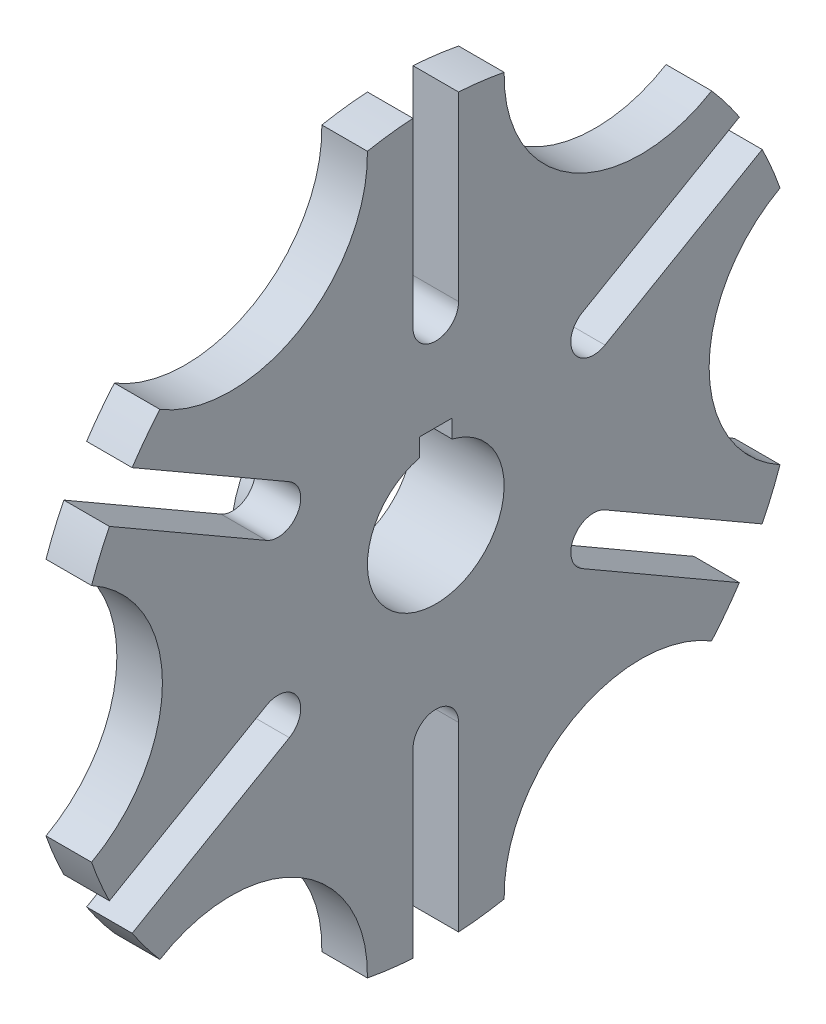
SolidWorks part; units mm, degrees
ref_plane "Front" through (0, 0, 0) normal (0, 0, 1) x (1, 0, 0)
ref_plane "Top" through (0, 0, 0) normal (0, 1, 0) x (1, 0, 0)
ref_plane "Right" through (0, 0, 0) normal (1, 0, 0) x (0, 0, -1)
sketch "Sketch1" plane through (0, 0, 0) normal (1, 0, 0) x (0, 0, -1)
  circle A0 centre (0, 0) radius 101.6
  dimension "D1" = 203.2
extrude "Boss-Extrude1" add sketch "Sketch1" along normal blind 12.7
sketch "Sketch2" plane through (12.7, 0, 0) normal (1, 0, 0) x (0, 0, -1)
  line L0 (0, 101.6) -> (0, 50.8) construction
  line L1 (6.35, 101.6) -> (6.35, 50.8)
  line L2 (-6.35, 101.6) -> (-6.35, 50.8)
  circle A0 centre (0, 0) radius 50.8 construction
  circle A1 centre (0, 0) radius 101.6 construction
  arc A3 (-6.35, 50.8) -> (6.35, 50.8) centre (0, 50.8) ccw
  point P7 (0, 76.2)
  dimension "D1" = 101.6
  dimension "D2" = 12.7
extrude "Cut-Extrude1" cut sketch "Sketch2" against normal through all and the other way through all
pattern_circular "CirPattern1" count 6 over 360 about axis through (12.7, 0, 0) along (-1, 0, 0) of "Cut-Extrude1"
sketch "Sketch3" plane through (12.7, 0, 0) normal (1, 0, 0) x (0, 0, -1)
  circle A0 centre (0, 0) radius 114.3
  circle A1 centre (-114.3, 0) radius 38.1
  arc M15 (-90.9912, 45.2014) -> (-90.9912, -45.2014) centre (0, 0) ccw
  dimension "D1" = 114.3
  dimension "D2" = 38.1
extrude "Cut-Extrude2" cut sketch "Sketch3" against normal blind 12.7 contours A1 M15
pattern_circular "CirPattern2" count 6 over 360 about axis through (0, 0, 0) along (1, 0, 0) of "Cut-Extrude2"
sketch "Sketch4" plane through (12.7, 0, 0) normal (1, 0, 0) x (0, 0, -1)
  circle A0 centre (0, 0) radius 31.75
  dimension "D1" = 63.5
extrude "Boss-Extrude2" add sketch "Sketch4" against normal blind 25.4
sketch "Sketch7" plane through (-12.7, 0, 0) normal (-1, 0, 0) x (0, 0, 1)
  line L0 (0, 0) -> (0, -8.9704)
  line L1 (0, -8.9704) -> (4.572, -8.9704)
  line L2 (4.572, -8.9704) -> (4.572, 18.4932)
  line L4 (4.572, 18.4932) -> (-4.572, 18.4932)
  line L5 (4.572, 18.4932) -> (4.572, 23.5732)
  line L6 (4.572, 23.5732) -> (-4.572, 23.5732)
  line L7 (-4.572, 18.4932) -> (-4.572, 23.5732)
  circle A0 centre (0, 0) radius 19.05
  dimension "D1" = 38.1
  dimension "D2" = 4.572
  dimension "D3" = 9.144
  dimension "D4" = 5.08
extrude "Cut-Extrude5" cut sketch "Sketch7" against normal through all
fillet "Fillet1" radius 6.35 1 edges at (0, 0, -31.75)
